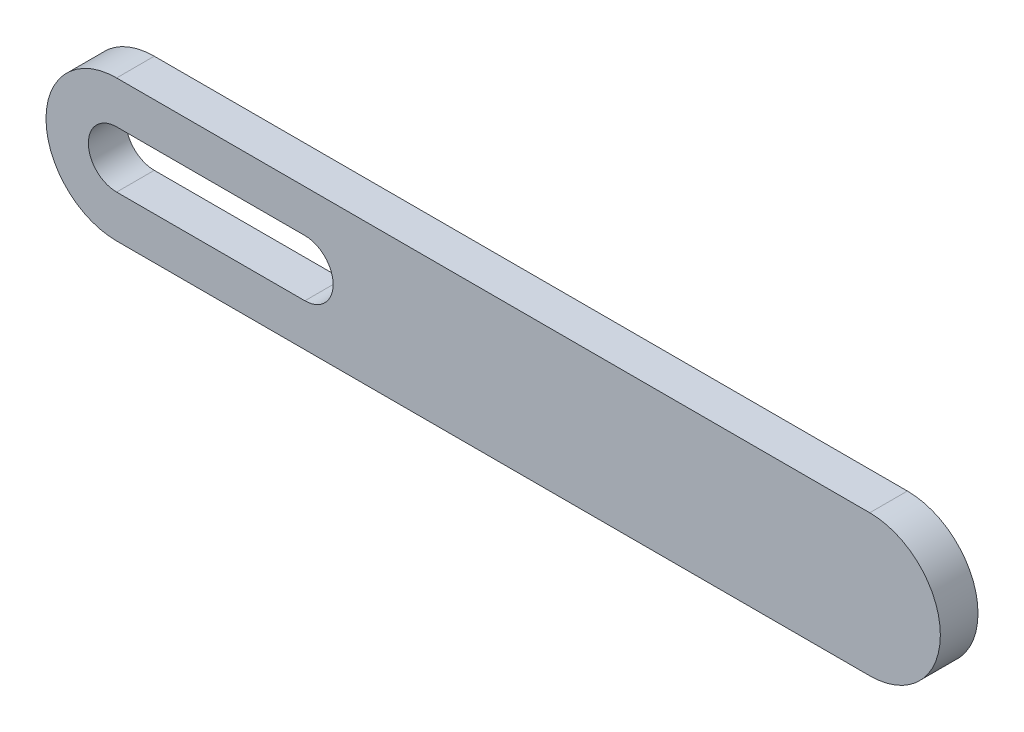
SolidWorks part; units mm, degrees
ref_plane "Front Plane" through (0, 0, 0) normal (0, 0, 1) x (1, 0, 0)
ref_plane "Top Plane" through (0, 0, 0) normal (0, 1, 0) x (1, 0, 0)
ref_plane "Right Plane" through (0, 0, 0) normal (1, 0, 0) x (0, 0, -1)
sketch "Sketch1" plane through (0, 0, 0) normal (0, 0, 1) x (1, 0, 0)
  line L0 (0, 0) -> (400, 0) construction
  line L1 (0, 37.5) -> (400, 37.5)
  line L2 (0, -37.5) -> (400, -37.5)
  line L3 (0, 0) -> (100, 0) construction
  line L4 (0, 15) -> (100, 15)
  line L5 (0, -15) -> (100, -15)
  arc A0 (0, 37.5) -> (0, -37.5) centre (0, 0) ccw
  arc A1 (400, -37.5) -> (400, 37.5) centre (400, 0) ccw
  arc A2 (0, 15) -> (0, -15) centre (0, 0) ccw
  arc A3 (100, -15) -> (100, 15) centre (100, 0) ccw
  point P3 (200, 0)
  point P10 (50, 0)
  dimension "D4" = 15
  dimension "D1" = 400
  dimension "D2" = 75
  dimension "D3" = 100
extrude "Boss-Extrude1" add sketch "Sketch1" along normal mid plane 20
